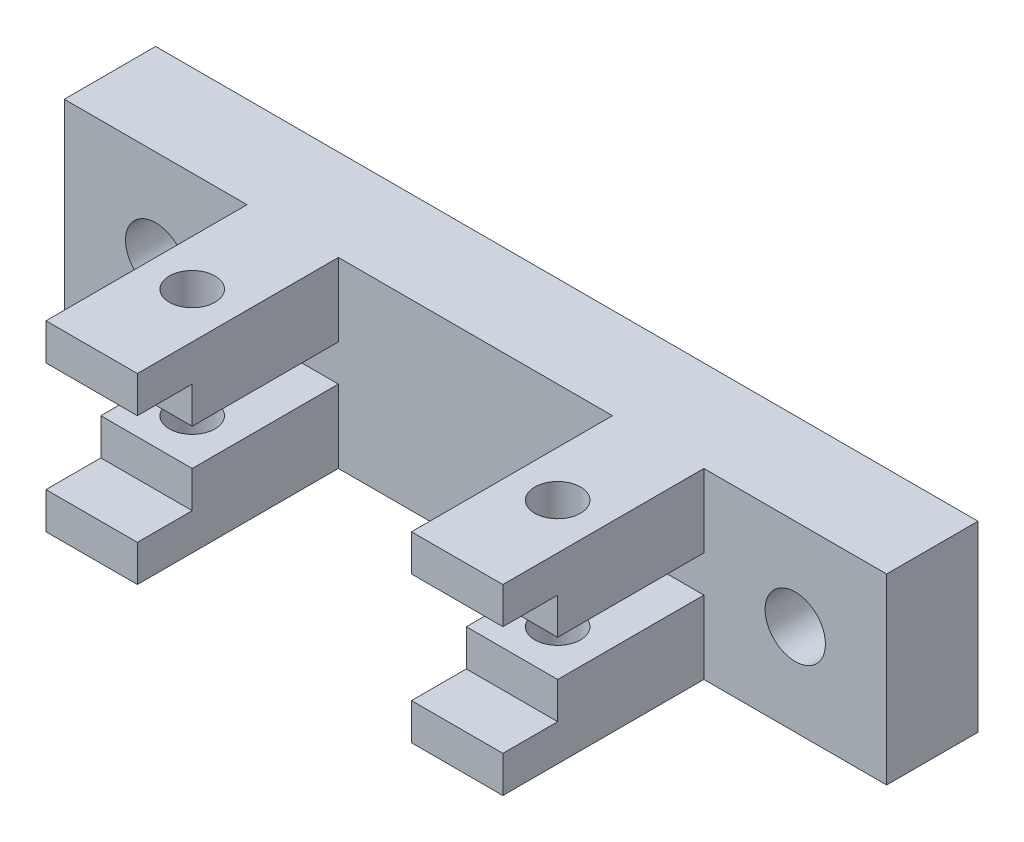
SolidWorks part; units mm, degrees
material "ABS"
ref_plane "Front" through (0, 0, 0) normal (0, 0, 1) x (1, 0, 0)
ref_plane "Top" through (0, 0, 0) normal (0, 1, 0) x (1, 0, 0)
ref_plane "Right" through (0, 0, 0) normal (1, 0, 0) x (0, 0, -1)
sketch "Эскиз1" plane through (0, 0, 0) normal (0, 0, 1) x (1, 0, 0)
  line L1 (-22.5, 5) -> (22.5, 5)
  line L2 (-22.5, 5) -> (-22.5, -5)
  line L3 (-22.5, -5) -> (22.5, -5)
  line L4 (22.5, 5) -> (22.5, -5)
  line L5 (-22.5, 5) -> (22.5, -5) construction
  line L6 (-22.5, -5) -> (22.5, 5) construction
  point P0 (0, 0)
  dimension "D1" = 45
  dimension "D2" = 10
extrude "Бобышка-Вытянуть1" add sketch "Эскиз1" along normal blind 5
sketch "Эскиз2" plane through (0, 0, 5) normal (0, 0, 1) x (1, 0, 0)
  line L1 (22.5, 5) -> (-22.5, 5) construction
  line L2 (-12.5, 5) -> (-7.5, 5)
  line L3 (-12.5, 5) -> (-12.5, 1)
  line L4 (-12.5, 1) -> (-7.5, 1)
  line L5 (-7.5, 5) -> (-7.5, 1)
  line L6 (-22.5, 5) -> (-22.5, -5) construction
  line L7 (22.5, -5) -> (22.5, 5) construction
  line L8 (7.5, 5) -> (12.5, 5)
  line L9 (7.5, 5) -> (7.5, 1)
  line L10 (7.5, 1) -> (12.5, 1)
  line L11 (12.5, 5) -> (12.5, 1)
  dimension "D1" = 4
  dimension "D2" = 5
  dimension "D3" = 10
  dimension "D4" = 5
  dimension "D5" = 4
  dimension "D6" = 10
extrude "Бобышка-Вытянуть2" add sketch "Эскиз2" along normal blind 11
sketch "Эскиз3" plane through (0, 0, 16) normal (0, 0, 1) x (1, 0, 0)
  line L0 (-12.5, 5) -> (-12.5, 1) construction
  line L1 (-12.5, 3) -> (-7.5, 3)
  line L2 (-12.5, 3) -> (-12.5, 1)
  line L3 (-12.5, 1) -> (-7.5, 1)
  line L4 (-7.5, 3) -> (-7.5, 1)
extrude "Вырез-Вытянуть1" cut sketch "Эскиз3" against normal blind 3
sketch "Эскиз4" plane through (0, 0, 16) normal (0, 0, 1) x (1, 0, 0)
  line L0 (7.5, 5) -> (7.5, 1) construction
  line L1 (7.5, 3) -> (12.5, 3)
  line L2 (7.5, 3) -> (7.5, 1)
  line L3 (7.5, 1) -> (12.5, 1)
  line L4 (12.5, 3) -> (12.5, 1)
extrude "Вырез-Вытянуть2" cut sketch "Эскиз4" against normal blind 3
sketch "Эскиз5" plane through (0, 5, 0) normal (0, 1, 0) x (1, 0, 0)
  line L0 (-12.5, -16) -> (-12.5, -5) construction
  line L1 (7.5, -16) -> (7.5, -5) construction
  line L2 (-7.5, -16) -> (-12.5, -16) construction
  line L3 (12.5, -16) -> (7.5, -16) construction
  circle A0 centre (-10, -10.5) radius 1.25
  circle A1 centre (10, -10.5) radius 1.25
  point P10 (10, -16)
  dimension "D1" = 2.5
  dimension "D2" = 2.5
  dimension "D3" = 5.5
  dimension "D4" = 5.5
extrude "Вырез-Вытянуть3" cut sketch "Эскиз5" against normal blind 10
sketch "Эскиз6" plane through (0, 0, 5) normal (0, 0, 1) x (1, 0, 0)
  line L0 (-22.5, 5) -> (-22.5, -5) construction
  line L1 (22.5, -5) -> (22.5, 5) construction
  line L2 (22.5, 5) -> (12.5, 5) construction
  line L3 (-12.5, 5) -> (-22.5, 5) construction
  circle A0 centre (-17.5, 0) radius 1.65
  circle A1 centre (17.5, 0) radius 1.65
  point P4 (-22.5, 0)
  point P7 (22.5, 0)
  dimension "D1" = 5
  dimension "D2" = 5
  dimension "D3" = 5
  dimension "D4" = 5
extrude "Вырез-Вытянуть4" cut sketch "Эскиз6" against normal blind 5
sketch "Эскиз7" plane through (0, 0, 5) normal (0, 0, 1) x (1, 0, 0)
  line L0 (-22.5, -5) -> (22.5, -5) construction
  line L1 (-12.5, -5) -> (-7.5, -5)
  line L2 (-12.5, -5) -> (-12.5, -1)
  line L3 (-12.5, -1) -> (-7.5, -1)
  line L4 (-7.5, -5) -> (-7.5, -1)
  line L5 (-22.5, 5) -> (-22.5, -5) construction
  line L6 (22.5, -5) -> (22.5, 5) construction
  line L7 (7.5, -5) -> (12.5, -5)
  line L8 (7.5, -5) -> (7.5, -1)
  line L9 (7.5, -1) -> (12.5, -1)
  line L10 (12.5, -5) -> (12.5, -1)
  dimension "D1" = 5
  dimension "D2" = 4
  dimension "D3" = 10
  dimension "D4" = 5
  dimension "D5" = 4
  dimension "D6" = 10
extrude "Бобышка-Вытянуть3" add sketch "Эскиз7" along normal blind 11
sketch "Эскиз8" plane through (0, 0, 16) normal (0, 0, 1) x (1, 0, 0)
  line L0 (-7.5, -5) -> (-7.5, -1) construction
  line L1 (-12.5, -1) -> (-7.5, -1)
  line L2 (-12.5, -1) -> (-12.5, -3)
  line L3 (-12.5, -3) -> (-7.5, -3)
  line L4 (-7.5, -1) -> (-7.5, -3)
extrude "Вырез-Вытянуть5" cut sketch "Эскиз8" against normal blind 3
sketch "Эскиз9" plane through (0, 0, 16) normal (0, 0, 1) x (1, 0, 0)
  line L0 (12.5, -5) -> (12.5, -1) construction
  line L1 (7.5, -1) -> (12.5, -1)
  line L2 (7.5, -1) -> (7.5, -3)
  line L3 (7.5, -3) -> (12.5, -3)
  line L4 (12.5, -1) -> (12.5, -3)
extrude "Вырез-Вытянуть6" cut sketch "Эскиз9" against normal blind 3
sketch "Эскиз11" plane through (0, -5, 0) normal (0, -1, 0) x (1, 0, 0)
  line L0 (-12.5, 16) -> (-12.5, 5) construction
  line L1 (12.5, 16) -> (12.5, 5) construction
  line L2 (12.5, 5) -> (22.5, 5) construction
  line L3 (-7.5, 5) -> (7.5, 5) construction
  circle A0 centre (-10, 10.5) radius 1.25
  circle A1 centre (10, 10.5) radius 1.25
  dimension "D1" = 2.5
  dimension "D2" = 2.5
  dimension "D3" = 5.5
  dimension "D4" = 5.5
extrude "Вырез-Вытянуть7" cut sketch "Эскиз11" against normal blind 5
